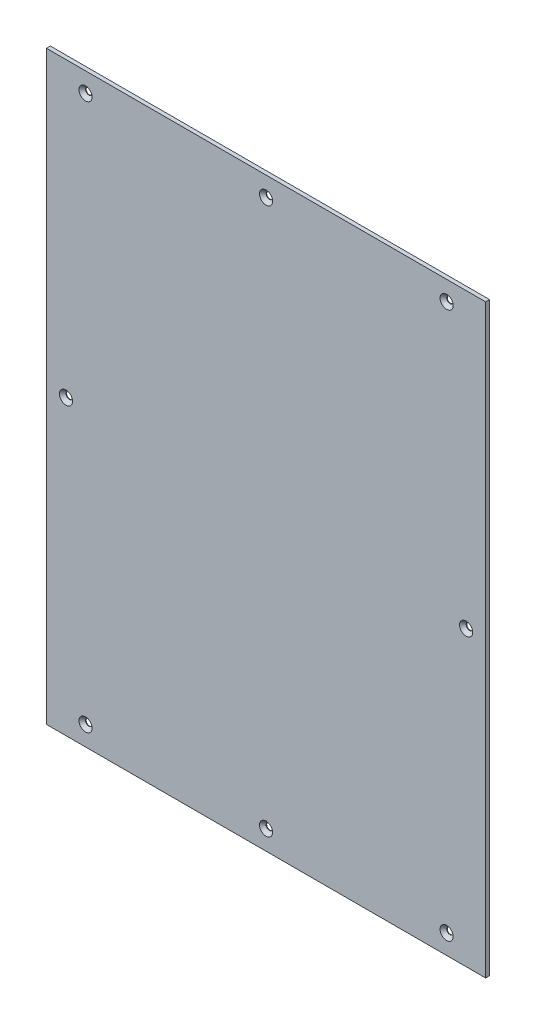
SolidWorks part; units mm, degrees
ref_plane "Front Plane" through (0, 0, 0) normal (0, 0, 1) x (1, 0, 0)
ref_plane "Top Plane" through (0, 0, 0) normal (0, 1, 0) x (1, 0, 0)
ref_plane "Right Plane" through (0, 0, 0) normal (1, 0, 0) x (0, 0, -1)
sketch "Sketch1" plane through (0, 0, 0) normal (0, 0, 1) x (1, 0, 0)
  line L1 (-225, -300) -> (225, -300)
  line L2 (-225, -300) -> (-225, 300)
  line L3 (-225, 300) -> (225, 300)
  line L4 (225, -300) -> (225, 300)
  line L5 (-225, -300) -> (225, 300) construction
  line L6 (-225, 300) -> (225, -300) construction
  point P0 (0, 0)
  dimension "D1" = 450
  dimension "D2" = 600
extrude "Boss-Extrude1" add sketch "Sketch1" along normal blind 4
sketch "Sketch2" plane through (0, 0, 4) normal (0, 0, 1) x (1, 0, 0)
  line L0 (-205, 378.3904) -> (-205, -313.5535) construction
  line L17 (-435.4748, 280) -> (450.358, 280) construction
  line L18 (-427.4037, -280) -> (432.8239, -280) construction
  line L19 (-225, 300) -> (-225, -300) construction
  line L20 (-225, -300) -> (225, -300) construction
  line L21 (225, 300) -> (-225, 300) construction
  line L22 (225, -300) -> (225, 300) construction
  line L23 (205, 365.8937) -> (205, -292.0763) construction
  point P32 (-185, -280)
  point P33 (185, -280)
  point P34 (-185, 280)
  point P35 (185, 280)
  point P36 (-205, 0)
  point P37 (205, 0)
  point P38 (0, 280)
  point P39 (0, -280)
  dimension "D2" = 40
  dimension "D3" = 40
  dimension "D4" = 40
  dimension "D5" = 40
  dimension "D6" = 300
  dimension "D7" = 20
  dimension "D8" = 300
  dimension "D9" = 20
  dimension "D10" = 20
  dimension "D11" = 20
  dimension "D18" = 0
  dimension "D19" = 0
hole_wizard "CSK for M6 Hex Socket Countersunk Cap Screw1" positions "Sketch3" profile "Sketch4" countersink size "M6" standard "ISO" end condition through all
sketch "Sketch3" plane through (0, 0, 4) normal (0, 0, 1) x (1, 0, 0)
  point P0 (-205, 0)
  point P3 (205, 0)
  point P6 (-185, -280)
  point P9 (0, -280)
  point P12 (185, -280)
  point P15 (185, 280)
  point P18 (0, 280)
  point P21 (-185, 280)
sketch "Sketch4" plane through (-205, 0, 4) normal (1, 0, 0) x (0, -1, 0)
  line L0 (0, 0) -> (0, 4)
  line L1 (0, 4) -> (3.3, 4)
  line L2 (3.3, 4) -> (3.3, 3.42)
  line L3 (3.3, 3.42) -> (6.72, 0)
  line L5 (6.72, 0) -> (0, 0)
  line L6 (-3.3, 3.42) -> (-6.72, 0) construction
  line L11 (0, -6.35) -> (0, 107.95) construction
  dimension "Thru Hole Dia." = 6.6
  dimension "Thru Hole Depth" = 4
  dimension "Near C'Sink Dia." = 13.44
  dimension "Near C'Sink Angle" = 90
